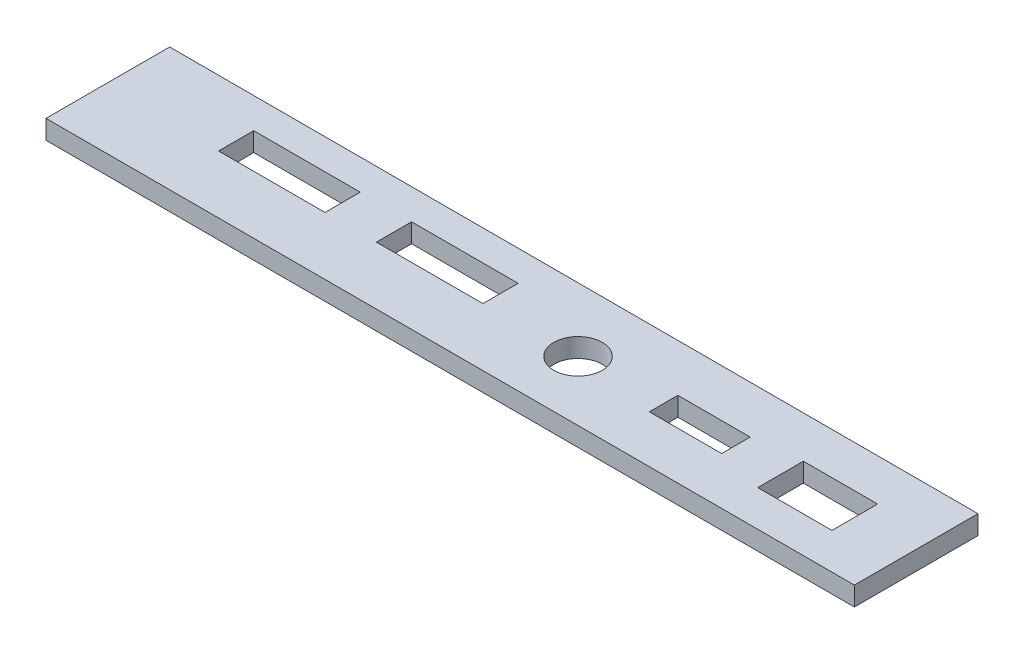
SolidWorks part; units mm, degrees
ref_plane "前视基准面" through (0, 0, 0) normal (0, 0, 1) x (1, 0, 0)
ref_plane "上视基准面" through (0, 0, 0) normal (0, 1, 0) x (1, 0, 0)
ref_plane "右视基准面" through (0, 0, 0) normal (1, 0, 0) x (0, 0, -1)
sketch "草图1" plane through (0, 0, 0) normal (0, 1, 0) x (1, 0, 0)
  line L0 (-10.0514, -3.9688) -> (74.9486, -3.9688) construction
  line L1 (-10.0514, 4.0312) -> (74.9486, 4.0312)
  line L2 (-10.0514, 4.0312) -> (-10.0514, -8.9688)
  line L3 (-10.0514, -8.9688) -> (74.9486, -8.9688)
  line L4 (74.9486, 4.0312) -> (74.9486, -8.9688)
  line L6 (68.7913, -5.1688) -> (60.9913, -5.1688)
  line L7 (68.7913, -5.1688) -> (68.7913, -0.3688)
  line L8 (68.7913, -0.3688) -> (60.9913, -0.3688)
  line L9 (60.9913, -5.1688) -> (60.9913, -0.3688)
  line L10 (68.7913, -5.1688) -> (60.9913, -0.3688) construction
  line L11 (68.7913, -0.3688) -> (60.9913, -5.1688) construction
  line L12 (55.9913, -3.9688) -> (48.3913, -3.9688)
  line L13 (55.9913, -3.9688) -> (55.9913, -0.9688)
  line L14 (55.9913, -0.9688) -> (48.3913, -0.9688)
  line L15 (48.3913, -3.9688) -> (48.3913, -0.9688)
  line L16 (55.9913, -3.9688) -> (48.3913, -0.9688) construction
  line L17 (55.9913, -0.9688) -> (48.3913, -3.9688) construction
  line L18 (29.7913, -2.8688) -> (18.5913, -2.8688)
  line L19 (29.7913, -2.8688) -> (29.7913, 0.8312)
  line L20 (29.7913, 0.8312) -> (18.5913, 0.8312)
  line L21 (18.5913, -2.8688) -> (18.5913, 0.8312)
  line L22 (29.7913, -2.8688) -> (18.5913, 0.8312) construction
  line L23 (29.7913, 0.8312) -> (18.5913, -2.8688) construction
  line L28 (1.9913, 0.8312) -> (13.1913, 0.8312)
  line L29 (1.9913, 0.8312) -> (1.9913, -2.8688)
  line L30 (1.9913, -2.8688) -> (13.1913, -2.8688)
  line L31 (13.1913, 0.8312) -> (13.1913, -2.8688)
  line L32 (1.9913, 0.8312) -> (13.1913, -2.8688) construction
  line L33 (1.9913, -2.8688) -> (13.1913, 0.8312) construction
  circle A0 centre (39.5913, -2.6688) radius 2.55
  point P4 (32.4486, 0.1541)
  point P11 (64.8913, -2.7688)
  point P16 (52.1913, -2.4688)
  point P19 (29.7913, -1.0188)
  point P24 (24.1913, -1.0188)
  point P29 (7.5913, -2.0287)
  point P42 (7.5913, -1.0188)
  dimension "D10" = 8.8
  dimension "D11" = 1.3
  dimension "D18" = 1.1
  dimension "D1" = 13
  dimension "D2" = 85
  dimension "D3" = 8
  dimension "D4" = 7.8
  dimension "D5" = 4.8
  dimension "D6" = 5
  dimension "D7" = 3
  dimension "D8" = 1.2
  dimension "D9" = 7.6
  dimension "D12" = 9.8
  dimension "D13" = 11.2
  dimension "D14" = 3.7
  dimension "D15" = 5.4
  dimension "D16" = 11.2
  dimension "D17" = 3.7
  dimension "D19" = 1.1
extrude "凸台-拉伸5" add sketch "草图1" along normal blind 2
